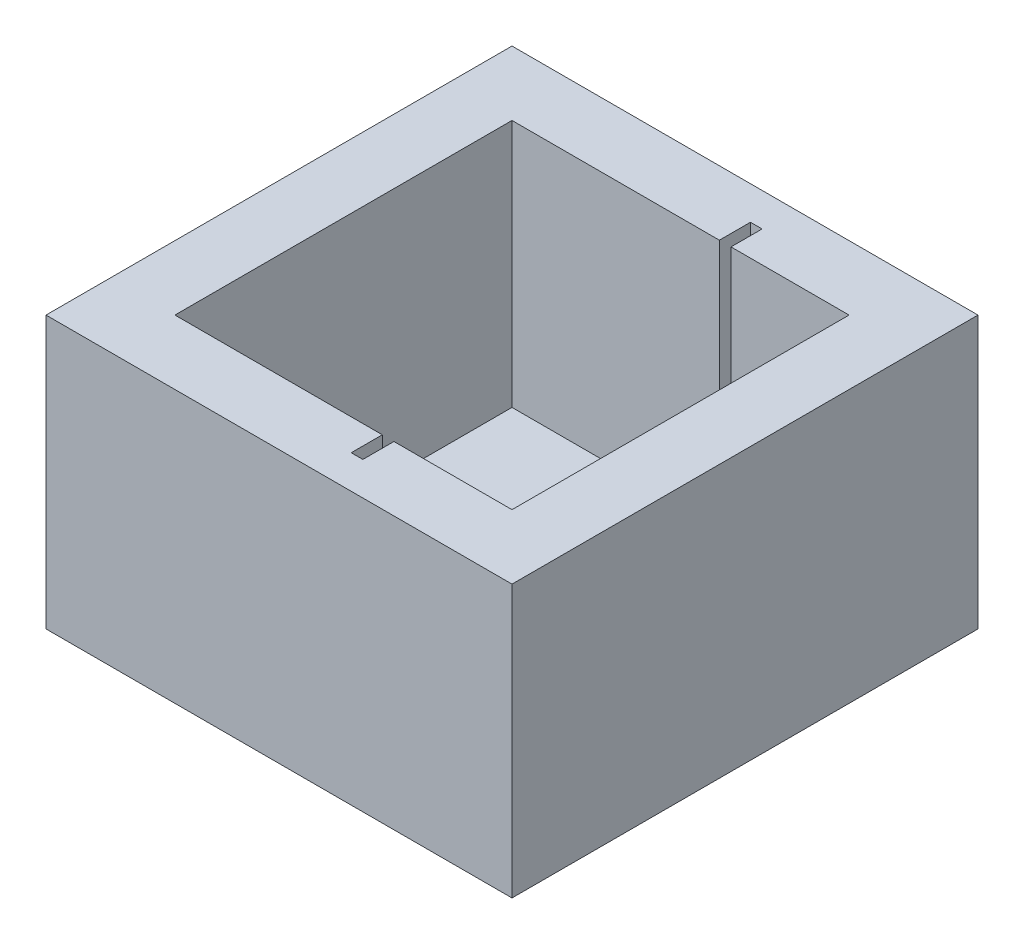
SolidWorks part; units mm, degrees
ref_plane "Front Plane" through (0, 0, 0) normal (0, 0, 1) x (1, 0, 0)
ref_plane "Top Plane" through (0, 0, 0) normal (0, 1, 0) x (1, 0, 0)
ref_plane "Right Plane" through (0, 0, 0) normal (1, 0, 0) x (0, 0, -1)
sketch "Sketch1" plane through (0, 0, 0) normal (0, 1, 0) x (1, 0, 0)
  line L1 (-34.2654, 18.6967) -> (25.7346, 18.6967)
  line L2 (-34.2654, 18.6967) -> (-34.2654, -41.3033)
  line L3 (-34.2654, -41.3033) -> (25.7346, -41.3033)
  line L4 (25.7346, 18.6967) -> (25.7346, -41.3033)
extrude "Boss-Extrude1" add sketch "Sketch1" along normal blind 35 contours L2 L1 L4 L3
sketch "Sketch2" plane through (0, 35, 0) normal (0, 1, 0) x (1, 0, 0)
  line L3 (-25.9654, 10.3967) -> (17.4346, 10.3967)
  line L4 (17.4346, 10.3967) -> (17.4346, -33.0033)
  line L5 (17.4346, -33.0033) -> (-25.9654, -33.0033)
  line L6 (-25.9654, -33.0033) -> (-25.9654, 10.3967)
extrude "Cut-Extrude1" cut sketch "Sketch2" against normal blind 32 contours L3 L4 L5 L6
sketch "Sketch3" plane through (0, 3, 0) normal (0, 1, 0) x (1, 0, 0)
  line L4 (-25.9654, 10.3967) -> (17.4346, 10.3967) construction
  line L5 (0.7346, 10.3967) -> (0.7346, 14.3967)
  line L6 (0.7346, 14.3967) -> (2.2346, 14.3967)
  line L7 (2.2346, 14.3967) -> (2.2346, 10.3967)
  line L8 (-25.9654, 10.3967) -> (17.4346, 10.3967) construction
  line L9 (2.2346, 10.3967) -> (0.7346, 10.3967)
  line L12 (17.4346, -33.0033) -> (-25.9654, -33.0033) construction
  line L13 (0.7346, -33.0033) -> (2.2346, -33.0033)
  line L14 (2.2346, -33.0033) -> (2.2346, -37.0033)
  line L15 (2.2346, -37.0033) -> (0.7346, -37.0033)
  line L16 (0.7346, -37.0033) -> (0.7346, -33.0033)
extrude "Cut-Extrude4" cut sketch "Sketch3" along normal blind 32
sketch "Sketch7" plane through (-34.2654, 0, 0) normal (-1, 0, 0) x (0, 0, 1)
  line L10 (-6.9967, 29) -> (-6.9967, 32.5)
  line L11 (-6.9967, 32.5) -> (-3.4967, 32.5)
  line L12 (-3.4967, 32.5) -> (-3.4967, 29)
  line L13 (-3.4967, 29) -> (-6.9967, 29)
extrude "Cut-Extrude7" cut sketch "Sketch7" against normal blind 76
sketch "Sketch9" plane through (-34.2654, 0, 0) normal (-1, 0, 0) x (0, 0, 1)
  line L1 (-6.9967, 33.3976) -> (-8.1978, 33.3976)
  line L2 (-8.1978, 33.3976) -> (-8.1978, 28.2498)
  line L3 (-8.1978, 28.2498) -> (-2.626, 28.2498)
  line L4 (-2.626, 28.2498) -> (-2.626, 33.3976)
  line L5 (-2.626, 33.3976) -> (-6.9967, 33.3976)
extrude "Boss-Extrude4" add sketch "Sketch9" against normal blind 8.3
sketch "Sketch10" plane through (25.7346, 0, 0) normal (1, 0, 0) x (0, 0, -1)
  line L1 (3.4967, 33.4242) -> (7.4491, 33.4242)
  line L2 (7.4491, 33.4242) -> (7.4491, 29.0244)
  line L3 (7.4491, 29.0244) -> (7.4491, 28.2433)
  line L4 (7.4491, 28.2433) -> (2.6542, 28.2433)
  line L5 (2.6542, 28.2433) -> (2.6542, 33.4242)
  line L6 (2.6542, 33.4242) -> (3.4967, 33.4242)
extrude "Boss-Extrude6" add sketch "Sketch10" against normal blind 8.3
